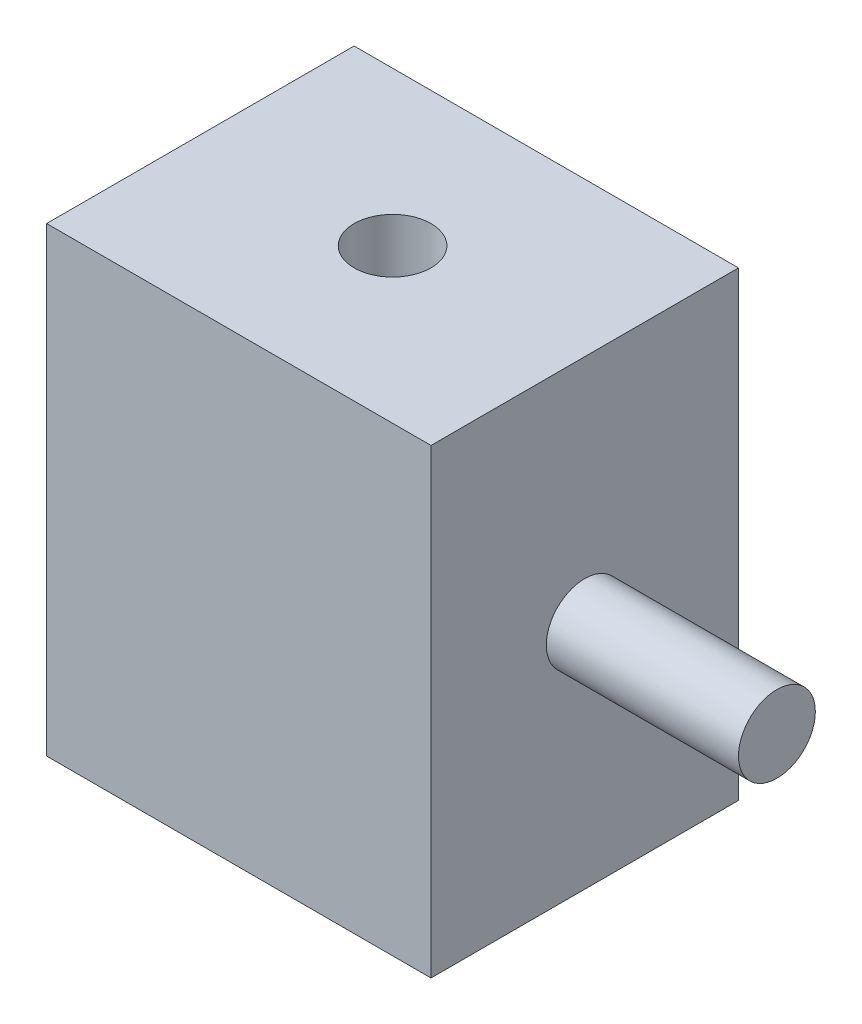
SolidWorks part; units mm, degrees
ref_plane "前视基准面" through (0, 0, 0) normal (0, 0, 1) x (1, 0, 0)
ref_plane "上视基准面" through (0, 0, 0) normal (0, 1, 0) x (1, 0, 0)
ref_plane "右视基准面" through (0, 0, 0) normal (1, 0, 0) x (0, 0, -1)
sketch "草图1" plane through (0, 0, 0) normal (0, 0, 1) x (1, 0, 0)
  line L1 (-5, -6) -> (5, -6)
  line L2 (-5, -6) -> (-5, 6)
  line L3 (-5, 6) -> (5, 6)
  line L4 (5, -6) -> (5, 6)
  line L5 (-5, -6) -> (5, 6) construction
  line L6 (-5, 6) -> (5, -6) construction
  point P0 (0, 0)
  dimension "D1" = 12
  dimension "D2" = 10
extrude "凸台-拉伸1" add sketch "草图1" along normal blind 8
sketch "草图3" plane through (5, 0, 0) normal (1, 0, 0) x (0, 0, -1)
  circle A0 centre (-20, 0) radius 5
  dimension "D1" = 10
sketch "草图4" plane through (5, 0, 0) normal (1, 0, 0) x (0, 0, -1)
  circle A0 centre (-2, 0) radius 2
  dimension "D1" = 4
sketch "草图5" plane through (5, 0, 0) normal (1, 0, 0) x (0, 0, -1)
  circle A0 centre (-4, 0) radius 1
  circle A1 centre (-2, 0) radius 2 construction
  dimension "D1" = 2
extrude "凸台-拉伸4" add sketch "草图5" along normal blind 5
sketch "草图6" plane through (0, -6, 0) normal (0, -1, 0) x (1, 0, 0)
  circle A0 centre (0, 4) radius 1
  dimension "D1" = 2
extrude "切除-拉伸1" cut sketch "草图6" against normal blind 16
